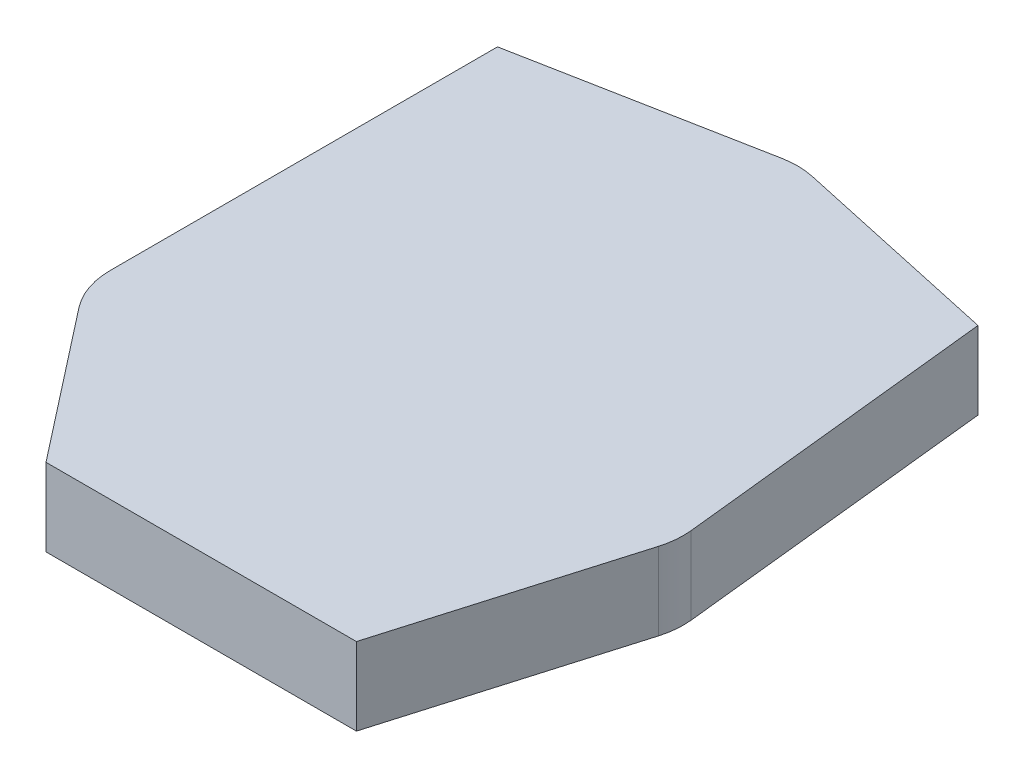
SolidWorks part; units mm, degrees
ref_plane "Спереди" through (0, 0, 0) normal (0, 0, 1) x (1, 0, 0)
ref_plane "Сверху" through (0, 0, 0) normal (0, 1, 0) x (1, 0, 0)
ref_plane "Справа" through (0, 0, 0) normal (1, 0, 0) x (0, 0, -1)
sketch "Эскиз1" plane through (0, 0, 0) normal (0, 1, 0) x (1, 0, 0)
  line L0 (0, 0) -> (-25.9098, 33.1745)
  line L1 (-25.9098, 33.1745) -> (-25.9098, 113.1745)
  line L2 (-25.9098, 113.1745) -> (23.2007, 122.5633)
  line L3 (23.2007, 122.5633) -> (67.1671, 112.9736)
  line L4 (67.1671, 112.9736) -> (74.0902, 47.9736)
  line L5 (74.0902, 47.9736) -> (60, 0)
  line L6 (60, 0) -> (0, 0)
  dimension "D1" = 80
  dimension "D2" = 50
  dimension "D3" = 45
  dimension "D4" = 65
  dimension "D5" = 50
  dimension "D6" = 60
extrude "Бобышка-Вытянуть1" add sketch "Эскиз1" along normal blind 15
fillet "Скругление1" radius 15 1 edges at (-25.9098, 7.5, -33.1745)
fillet "Скругление2" radius 15 1 edges at (74.0902, 7.5, -47.9736)
fillet "Скругление3" radius 15 1 edges at (23.2007, 7.5, -122.5633)
